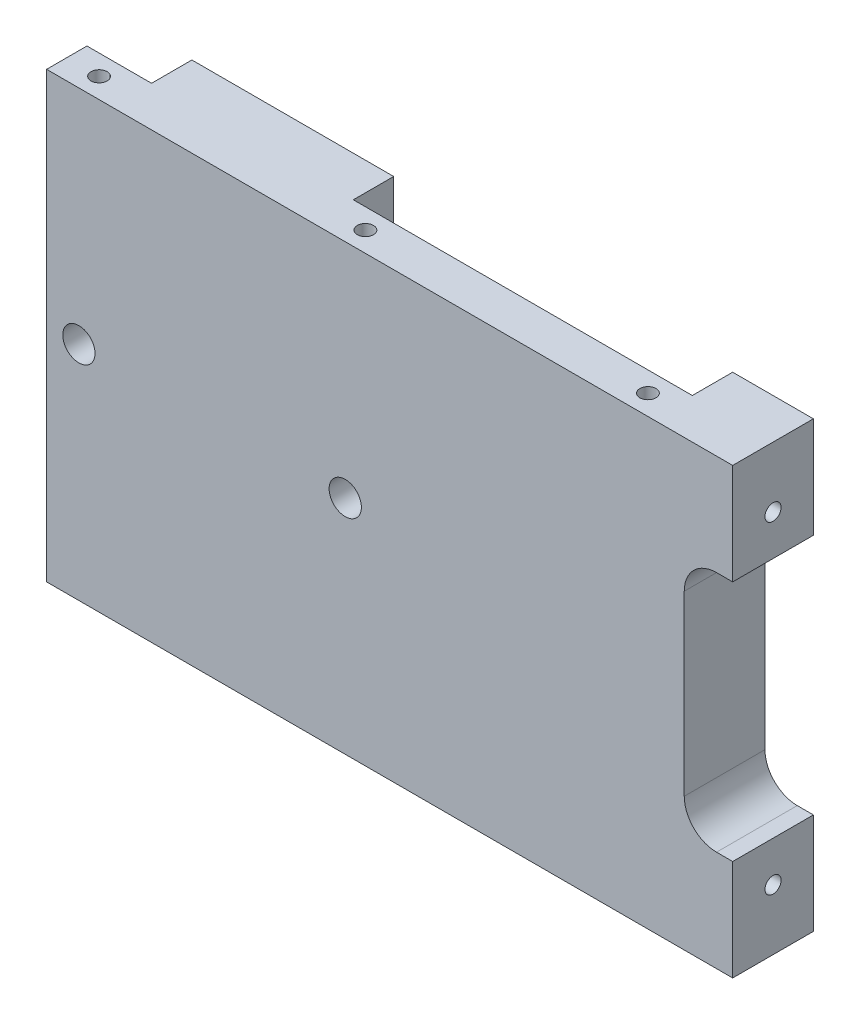
SolidWorks part; units mm, degrees
material "PE haute densité"
ref_plane "Plan de face" through (0, 0, 0) normal (0, 0, 1) x (1, 0, 0)
ref_plane "Plan de dessus" through (0, 0, 0) normal (0, 1, 0) x (1, 0, 0)
ref_plane "Plan de droite" through (0, 0, 0) normal (1, 0, 0) x (0, 0, -1)
sketch "Esquisse1" plane through (0, 0, 0) normal (0, 0, 1) x (1, 0, 0)
  line L1 (0, -27.5) -> (85, -27.5)
  line L2 (0, -27.5) -> (0, 27.5)
  line L3 (0, 27.5) -> (85, 27.5)
  line L4 (85, -27.5) -> (85, 27.5)
  dimension "D1" = 55
  dimension "D2" = 85
extrude "Boss.-Extru.1" add sketch "Esquisse1" along normal blind 10
sketch "Esquisse2" plane through (0, 27.5, 0) normal (0, 1, 0) x (1, 0, 0)
  line L0 (85, 0) -> (0, 0) construction
  line L1 (0, 0) -> (8, 0)
  line L2 (0, 0) -> (0, -5)
  line L3 (0, -5) -> (8, -5)
  line L4 (8, 0) -> (8, -5)
  line L5 (33, 0) -> (75, 0)
  line L6 (33, 0) -> (33, -5)
  line L7 (33, -5) -> (75, -5)
  line L8 (75, 0) -> (75, -5)
  line L9 (85, -10) -> (0, -10) construction
  dimension "D1" = 5
  dimension "D2" = 8
  dimension "D3" = 25
  dimension "D4" = 42
extrude "Enlèv. mat.-Extru.1" cut sketch "Esquisse2" against normal through all
sketch "Esquisse3" plane through (0, 0, 10) normal (0, 0, 1) x (1, 0, 0)
  line L0 (0, 0) -> (4, 0) construction
  line L1 (0, 27.5) -> (0, -27.5) construction
  line L2 (4, 0) -> (37, 0) construction
  circle A0 centre (4, 0) radius 2
  circle A1 centre (37, 0) radius 2
  dimension "D1" = 33
  dimension "D2" = 4
  dimension "D3" = 4
extrude "Enlèv. mat.-Extru.2" cut sketch "Esquisse3" against normal through all
hole_wizard "Trou taraudé M3x0.51" positions "Esquisse5" profile "Esquisse4" tap size "M3x0.5" standard "Ansi Metric"
sketch "Esquisse5" plane through (0, -27.5, 0) normal (0, -1, 0) x (-1, 0, 0)
  line L0 (-4, -7.5) -> (-37, -7.5) construction
  line L1 (-37, -7.5) -> (-72, -7.5) construction
  line L3 (0, -10) -> (-85, -10) construction
  line L6 (0, -10) -> (0, -5) construction
  point P0 (-4, -7.5)
  point P2 (-37, -7.5)
  point P4 (-72, -7.5)
  dimension "D1" = 2.5
  dimension "D2" = 4
  dimension "D3" = 33
  dimension "D4" = 35
sketch "Esquisse4" plane through (4, -27.5, 7.5) normal (1, 0, 0) x (0, 0, -1)
  line L0 (0, 0) -> (0, 15.6009)
  line L1 (0, 15.6009) -> (1, 15)
  line L2 (1, 15) -> (1, 0)
  line L5 (1, 0) -> (0, 0)
  line L10 (0, 15.6009) -> (-1, 15) construction
  line L11 (0, -6.35) -> (0, 107.95) construction
  dimension "Diamètre du trou pour taraudage" = 2
  dimension "Profondeur du trou pour taraudage" = 15
  dimension "Angle de pointe" = 118
cosmetic thread "Filetage de perçage1" parameters "D1"=10, "D2"=3
cosmetic thread "Filetage de perçage2" parameters "D1"=10, "D2"=3
cosmetic thread "Filetage de perçage3" parameters "D1"=10, "D2"=3
mirror "Symétrie1" about plane through (0, 0, 0) normal (0, 1, 0) of "Trou taraudé M3x0.51"
hole_wizard "Trou taraudé M3x0.52" positions "Esquisse7" profile "Esquisse6" tap size "M3x0.5" standard "Ansi Metric"
sketch "Esquisse7" plane through (85, 0, 0) normal (1, 0, 0) x (0, 0, -1)
  line L0 (-5, 20) -> (-5, -20) construction
  line L2 (0, 0) -> (-10, 0) construction
  line L4 (-10, -27.5) -> (-10, 27.5) construction
  line L5 (0, -27.5) -> (0, 27.5) construction
  point P0 (-5, 20)
  point P2 (-5, -20)
  point P18 (-5, 0)
  dimension "D1" = 40
sketch "Esquisse6" plane through (85, 20, 5) normal (0, 1, 0) x (0, 0, -1)
  line L0 (0, 0) -> (0, 12.6009)
  line L1 (0, 12.6009) -> (1, 12)
  line L2 (1, 12) -> (1, 0)
  line L5 (1, 0) -> (0, 0)
  line L10 (0, 12.6009) -> (-1, 12) construction
  line L11 (0, -6.35) -> (0, 107.95) construction
  dimension "Diamètre du trou pour taraudage" = 2
  dimension "Profondeur du trou pour taraudage" = 12
  dimension "Angle de pointe" = 118
cosmetic thread "Filetage de perçage4" parameters "D1"=10, "D2"=3
cosmetic thread "Filetage de perçage5" parameters "D1"=10, "D2"=3
sketch "Esquisse8" plane through (0, -27.5, 0) normal (0, -1, 0) x (1, 0, 0)
  line L0 (8, 0) -> (33, 0) construction
  line L1 (0, 10) -> (30, 10)
  line L2 (0, 10) -> (0, 0)
  line L3 (0, 0) -> (30, 0)
  line L4 (30, 10) -> (30, 0)
  line L5 (33, 0) -> (33, 5) construction
  dimension "D1" = 3
extrude "Enlèv. mat.-Extru.3" [suppressed] cut sketch "Esquisse8" against normal through all
sketch "Esquisse9" plane through (0, 0, 10) normal (0, 0, 1) x (1, 0, 0)
  line L0 (85, -27.5) -> (85, 27.5) construction
  line L1 (85, -15) -> (79, -15)
  line L2 (85, -15) -> (85, 15)
  line L3 (85, 15) -> (79, 15)
  line L4 (79, -15) -> (79, 15)
  point P4 (85, 0)
  dimension "D1" = 30
  dimension "D2" = 6
extrude "Enlèv. mat.-Extru.4" cut sketch "Esquisse9" against normal through all
fillet "Congé1" radius 4 2 edges at (79, 15, 5) (79, -15, 5)
